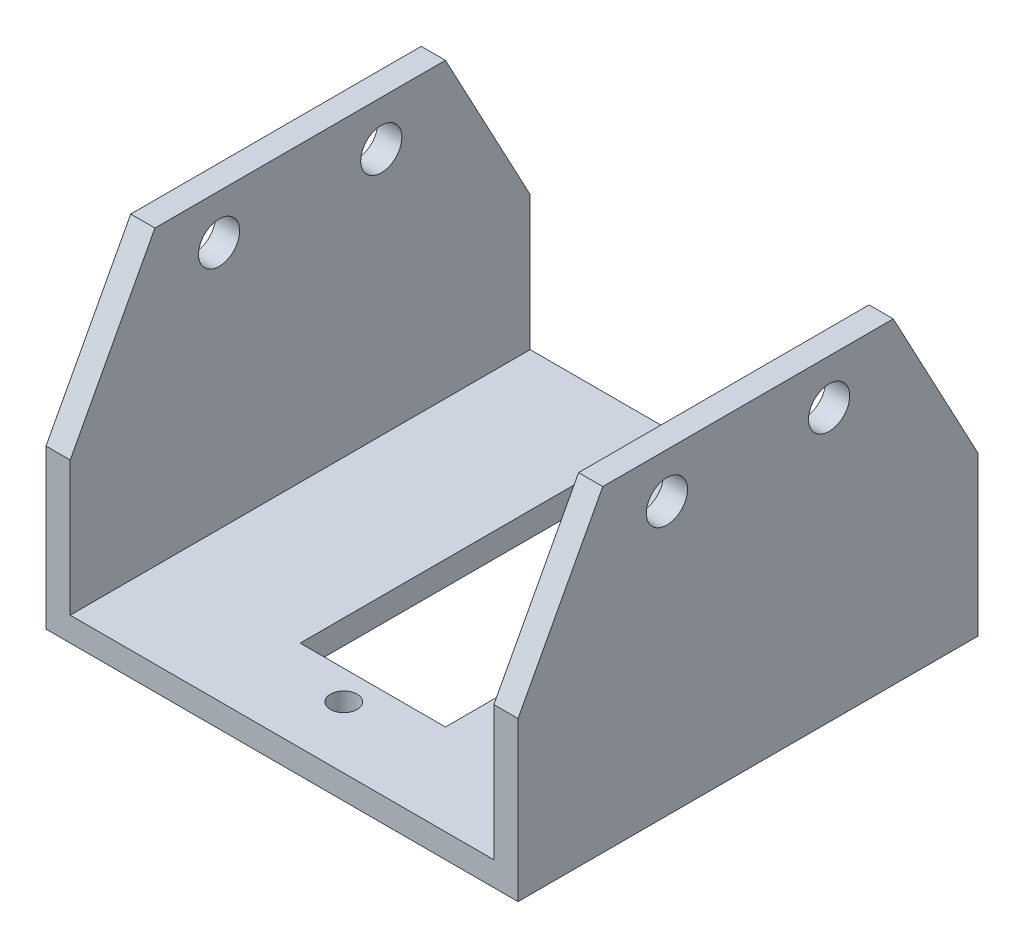
SolidWorks part; units mm, degrees
ref_plane "前视基准面" through (0, 0, 0) normal (0, 0, 1) x (1, 0, 0)
ref_plane "上视基准面" through (0, 0, 0) normal (0, 1, 0) x (1, 0, 0)
ref_plane "右视基准面" through (0, 0, 0) normal (1, 0, 0) x (0, 0, -1)
other "Configuration Table"
sketch "草图2" plane through (0, 0, 0) normal (0, 1, 0) x (1, 0, 0)
  line L4 (-21.7268, -11.4852) -> (-21.7268, -37.9419) construction
  line L6 (-49.5541, -23.6009) -> (15.72, -23.6009) construction
  line L10 (-15.7268, -35.1009) -> (-15.7268, -12.1009)
  line L11 (-27.7268, -35.1009) -> (-27.7268, -12.1009)
  line L12 (-27.7268, -12.1009) -> (-15.7268, -12.1009)
  line L13 (-27.7268, -35.1009) -> (-15.7268, -35.1009)
  line L14 (-39.2268, -4.6009) -> (-4.2268, -4.6009)
  line L22 (-39.2268, -42.6009) -> (-4.2268, -42.6009)
  line L23 (-39.2268, -4.6009) -> (-41.2268, -4.6009)
  line L24 (-41.2268, -4.6009) -> (-41.2268, -42.6009)
  line L26 (-41.2268, -42.6009) -> (-39.2268, -42.6009)
  line L27 (-2.2268, -4.6009) -> (-2.2268, -42.6009)
  line L28 (-4.2268, -4.6009) -> (-2.2268, -4.6009)
  line L29 (-4.2268, -42.6009) -> (-2.2268, -42.6009)
  circle A5 centre (-21.7268, -9.7009) radius 1.1
  circle A6 centre (-21.7268, -37.5009) radius 1.1
  point P7 (-21.7268, -4.6009)
  point P18 (-48.4768, -23.6009)
  point P20 (-15.7268, -23.6009)
  dimension "D1" = 6
  dimension "D3" = 13.9
  dimension "D4" = 11.5
extrude "凸台-拉伸2" add sketch "草图2" along normal blind 2
sketch "草图4" plane through (0, 2, 0) normal (0, 1, 0) x (1, 0, 0)
  line L0 (-41.2268, -4.6009) -> (-39.2268, -4.6009)
  line L1 (-2.2268, -4.6009) -> (-41.2268, -4.6009) construction
  line L2 (-39.2268, -4.6009) -> (-39.2268, -42.6009)
  line L3 (-41.2268, -42.6009) -> (-2.2268, -42.6009) construction
  line L4 (-39.2268, -42.6009) -> (-41.2268, -42.6009)
  line L5 (-41.2268, -42.6009) -> (-41.2268, -4.6009)
  dimension "D1" = 2
extrude "凸台-拉伸3" add sketch "草图4" along normal blind 24.2
sketch "草图5" plane through (0, 2, 0) normal (0, 1, 0) x (1, 0, 0)
  line L0 (-2.2268, -4.6009) -> (-2.2268, -42.6009)
  line L1 (-2.2268, -42.6009) -> (-4.2268, -42.6009)
  line L2 (-39.2268, -42.6009) -> (-2.2268, -42.6009) construction
  line L3 (-4.2268, -42.6009) -> (-4.2268, -4.6009)
  line L4 (-2.2268, -4.6009) -> (-39.2268, -4.6009) construction
  line L5 (-4.2268, -4.6009) -> (-2.2268, -4.6009)
  dimension "D1" = 2
extrude "凸台-拉伸4" add sketch "草图5" along normal blind 24.2
sketch "草图6" plane through (-2.2268, 0, 0) normal (1, 0, 0) x (0, 0, -1)
  line L0 (-23.6009, 26.3896) -> (-23.6009, -4.1353) construction
  line L1 (-42.6009, 26.2) -> (-4.6009, 26.2) construction
  circle A0 centre (-30.3009, 22.5) radius 1.7
  circle A1 centre (-16.9009, 22.5) radius 1.7
  dimension "D1" = 6.7
  dimension "D2" = 3.7
extrude "切除-拉伸1" cut sketch "草图6" against normal blind 50
sketch "草图7" plane through (-2.2268, 0, 0) normal (1, 0, 0) x (0, 0, -1)
  line L1 (-42.6009, 26.2) -> (-4.6009, 26.2) construction
  line L2 (-35.6009, 26.2) -> (-42.6009, 13.1)
  line L3 (-42.6009, 26.2) -> (-42.6009, 0) construction
  line L5 (-11.6009, 26.2) -> (-4.6009, 13.1)
  line L6 (-4.6009, 26.2) -> (-4.6009, 0) construction
  line L7 (-35.6009, 26.2) -> (-42.6009, 26.2)
  line L8 (-42.6009, 26.2) -> (-42.6009, 13.1)
  line L9 (-11.6009, 26.2) -> (-4.6009, 26.2)
  line L10 (-4.6009, 26.2) -> (-4.6009, 13.1)
extrude "切除-拉伸2" cut sketch "草图7" against normal blind 39
